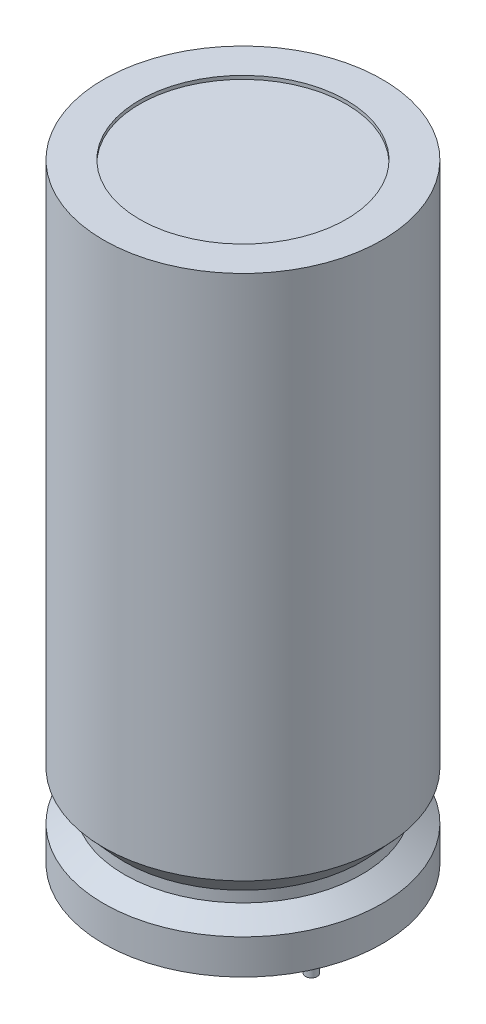
SolidWorks part; units mm, degrees
ref_plane "前视基准面" through (0, 0, 0) normal (0, 0, 1) x (1, 0, 0)
ref_plane "上视基准面" through (0, 0, 0) normal (0, 1, 0) x (1, 0, 0)
ref_plane "右视基准面" through (0, 0, 0) normal (1, 0, 0) x (0, 0, -1)
sketch "草图1" plane through (0, 0, 0) normal (0, 0, 1) x (1, 0, 0)
  line L0 (0, 0) -> (-8, 0)
  line L1 (-8, 0) -> (-8, 2)
  line L2 (-8, 2) -> (-6.8091, 2.8476)
  line L3 (-6.8091, 2.8476) -> (-6.8091, 3.4784)
  line L4 (-6.8091, 3.4784) -> (-8, 4.7841)
  line L5 (-8, 4.7841) -> (-8, 35)
  line L6 (-8, 35) -> (0, 35)
  line L7 (0, 35) -> (0, 0)
  line L8 (0, 10.4273) -> (0, -11.0781) construction
  point P11 (-8, 5.0521)
  point P12 (-8, 7.0389)
  point P13 (0, 0)
  point P14 (-8.3902, 3.2865)
  point P15 (-8.228, 3.7731)
  point P16 (-8, 7.5618)
  point P17 (-6.8091, 5.8476)
  point P18 (-8, 7.2948)
  point P19 (-8, 5)
  point P20 (-8, 5.8894)
  point P21 (-8, 4.7841)
  dimension "D1" = 16
  dimension "D2" = 35
  dimension "D3" = 2
revolve "旋转1" add sketch "草图1" angle 360 about L8
sketch "草图2" plane through (0, 0, 0) normal (0, -1, 0) x (1, 0, 0)
  circle A0 centre (-3.5859, 0) radius 0.3373
  circle A1 centre (3.9292, 0) radius 0.3329
extrude "凸台-拉伸1" add sketch "草图2" along normal blind 3.5
sketch "草图3" plane through (0, 35, 0) normal (0, 1, 0) x (1, 0, 0)
  circle A0 centre (0, 0) radius 5.9345
extrude "切除-拉伸1" cut sketch "草图3" against normal blind 0.2
sketch "草图4" plane through (0, 0, 0) normal (0, -1, 0) x (1, 0, 0)
  circle A0 centre (0, 0) radius 5.5306
extrude "切除-拉伸2" cut sketch "草图4" against normal blind 0.2
